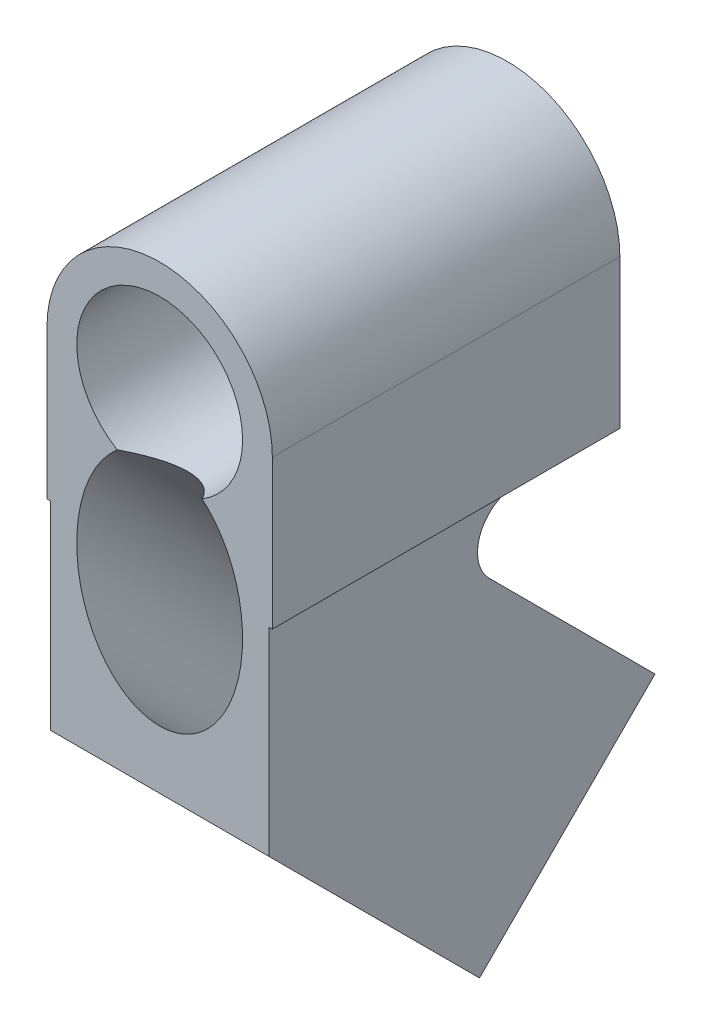
SolidWorks part; units mm, degrees
ref_plane "Alzado" through (0, 0, 0) normal (0, 0, 1) x (1, 0, 0)
ref_plane "Planta" through (0, 0, 0) normal (0, 1, 0) x (1, 0, 0)
ref_plane "Vista lateral" through (0, 0, 0) normal (1, 0, 0) x (0, 0, -1)
sketch "Croquis1" plane through (0, 0, 0) normal (0, 0, 1) x (1, 0, 0)
  line L0 (0, 0) -> (0, -15) construction
  line L1 (-11.35, -15) -> (11.35, -15)
  line L2 (-11.35, -15) -> (-11.35, 0)
  line L3 (11.35, -15) -> (11.35, 0)
  circle A0 centre (0, 0) radius 8.35
  arc A1 (11.35, 0) -> (-11.35, 0) centre (0, 0) ccw
  point P8 (0, -15)
  dimension "D1" = 16.7
  dimension "D2" = 3
  dimension "D3" = 15
extrude "Saliente-Extruir1" add sketch "Croquis1" against normal mid plane 35
ref_plane "Plano1" through (0, -15, 0) normal (0, -1, 0) x (-1, 0, 0)
sketch "Croquis2" plane through (0, 0, 0) normal (1, 0, 0) x (0, 0, -1)
  line L0 (-17.5, -15) -> (-17.5, -35)
  line L1 (-17.5, -35) -> (3.7132, -56.2132)
  line L4 (17.5, -15) -> (-17.5, -15) construction
  line L5 (3.7132, -56.2132) -> (21.3909, -38.5355)
  line L6 (12.552, -47.3744) -> (-17.5, -17.3223) construction
  line L7 (-17.5, -15) -> (7.5122, -15)
  line L8 (4.6838, -21.8284) -> (21.3909, -38.5355)
  arc A0 (4.6838, -21.8284) -> (7.5122, -15) centre (7.5122, -19) cw
  dimension "D3" = 4
  dimension "D1" = 135
  dimension "D2" = 25
  dimension "D4" = 30
  dimension "D5" = 20
extrude "Saliente-Extruir2" add sketch "Croquis2" along normal mid plane 22
ref_plane "Plano3" through (0, -29.9632, -29.9632) normal (0, -0.7071, -0.7071) x (-1, 0, 0)
sketch "Croquis4" plane through (0, -29.9632, -29.9632) normal (0, -0.7071, -0.7071) x (-1, 0, 0)
  line L0 (0, -12.1231) -> (0, -37.1231) construction
  line L1 (-11, -12.1231) -> (11, -12.1231) construction
  line L2 (-11, -37.1231) -> (11, -37.1231) construction
  circle A0 centre (0, -24.6231) radius 8.35
  dimension "D1" = 16.7
extrude "Cortar-Extruir1" cut sketch "Croquis4" against normal blind 55
